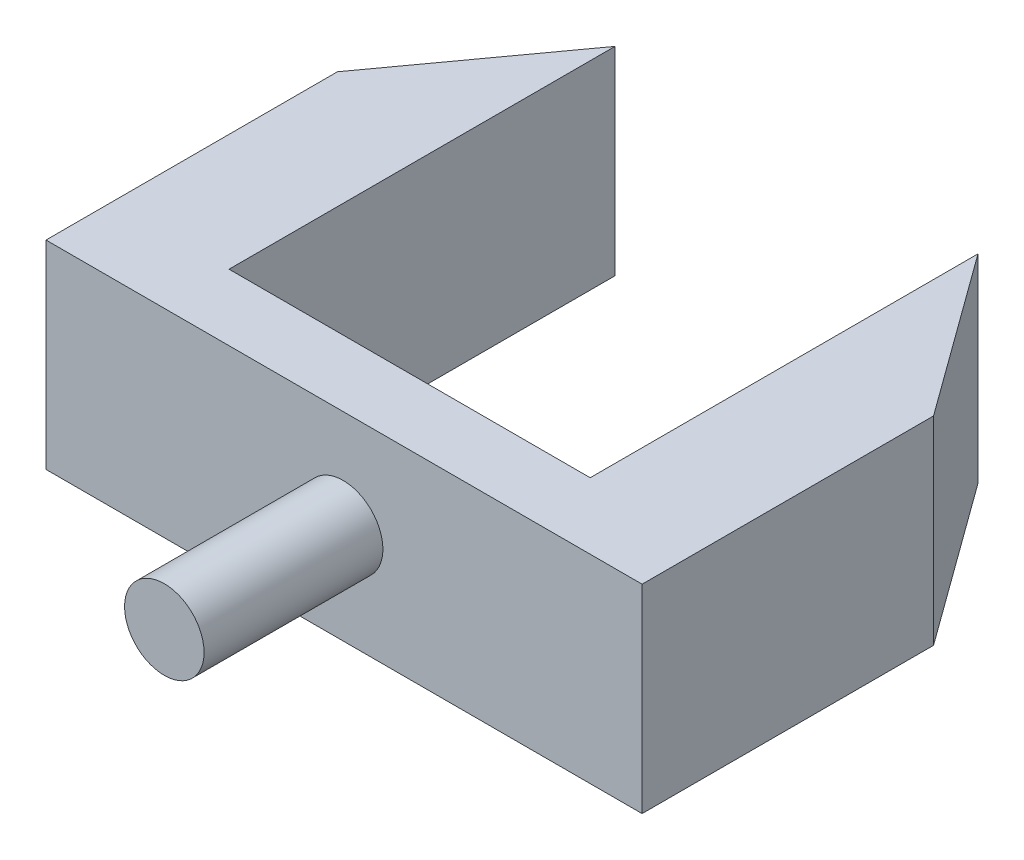
SolidWorks part; units mm, degrees
material "6061 Alloy"
ref_plane "Front Plane" through (0, 0, 0) normal (0, 0, 1) x (1, 0, 0)
ref_plane "Top Plane" through (0, 0, 0) normal (0, 1, 0) x (1, 0, 0)
ref_plane "Right Plane" through (0, 0, 0) normal (1, 0, 0) x (0, 0, -1)
sketch "Sketch3" plane through (0, 0, 0) normal (0, 1, 0) x (1, 0, 0)
  line L0 (-22.3624, 0) -> (22.6376, 0)
  line L1 (-22.3624, 0) -> (-22.3624, 22)
  line L2 (22.6376, 0) -> (22.6376, 22)
  line L3 (-22.3624, 22) -> (-13.5456, 34.1353)
  line L4 (22.6376, 22) -> (13.7189, 34.2755)
  line L5 (-13.5456, 34.1353) -> (-13.5456, 5)
  line L6 (-13.5456, 5) -> (13.7189, 5)
  line L7 (13.7189, 5) -> (13.7189, 34.2755)
  dimension "D1" = 45
  dimension "D2" = 5
  dimension "D4" = 144
  dimension "D5" = 15.1734
  dimension "144" = 144
  dimension "D6" = 15
extrude "Boss-Extrude1" add sketch "Sketch3" along normal blind 15
sketch "Sketch4" plane through (0, 0, 0) normal (0, 0, 1) x (1, 0, 0)
  line L0 (0, 0) -> (0.1376, 15) construction
  line L1 (-22.3624, 15) -> (22.6376, 15) construction
  circle A0 centre (0.0688, 7.5) radius 3
  dimension "D1" = 3
extrude "Boss-Extrude2" add sketch "Sketch4" along normal blind 13.5
